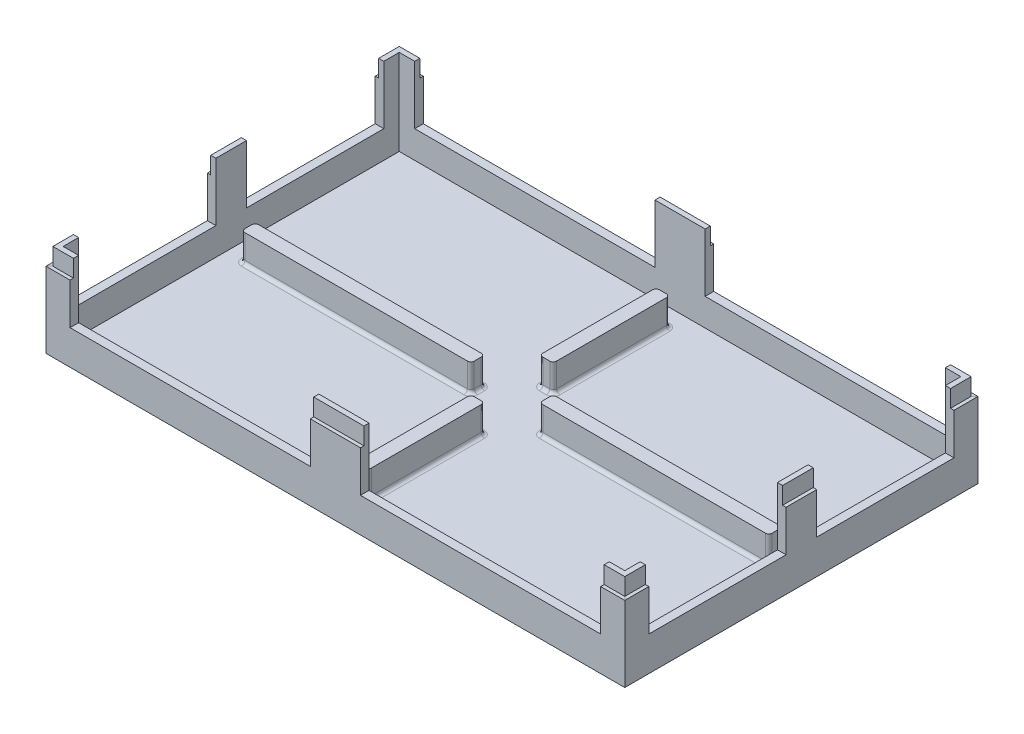
SolidWorks part; units mm, degrees
ref_plane "Front Plane" through (0, 0, 0) normal (0, 0, 1) x (1, 0, 0)
ref_plane "Top Plane" through (0, 0, 0) normal (0, 1, 0) x (1, 0, 0)
ref_plane "Right Plane" through (0, 0, 0) normal (1, 0, 0) x (0, 0, -1)
sketch "Sketch1" plane through (0, 0, 0) normal (0, 1, 0) x (1, 0, 0)
  line L0 (2, 48.96) -> (81.81, 48.96)
  line L1 (3, 47.46) -> (80.31, 47.46) construction
  line L2 (3, 47.46) -> (3, 3) construction
  line L3 (3, 3) -> (80.31, 3) construction
  line L4 (80.31, 47.46) -> (80.31, 3) construction
  line L5 (0, 50.46) -> (0, 60.2417) construction
  line L6 (80.31, -47.46) -> (80.31, -3) construction
  line L7 (3, -3) -> (80.31, -3) construction
  line L8 (3, -47.46) -> (3, -3) construction
  line L9 (3, -47.46) -> (80.31, -47.46) construction
  line L10 (-3, -47.46) -> (-80.31, -47.46) construction
  line L11 (-3, -47.46) -> (-3, -3) construction
  line L12 (-3, -3) -> (-80.31, -3) construction
  line L13 (-80.31, -47.46) -> (-80.31, -3) construction
  line L14 (-80.31, 47.46) -> (-80.31, 3) construction
  line L15 (-3, 3) -> (-80.31, 3) construction
  line L16 (-3, 47.46) -> (-3, 3) construction
  line L17 (-3, 47.46) -> (-80.31, 47.46) construction
  line L18 (-83.31, 50.46) -> (-83.31, -50.46)
  line L19 (2, -48.96) -> (81.81, -48.96)
  line L20 (-2, 48.96) -> (-2, 2)
  line L22 (2, 48.96) -> (2, 2)
  line L23 (81.81, 2) -> (2, 2)
  line L24 (-81.81, -48.96) -> (81.81, -48.96) construction
  line L25 (81.81, -2) -> (2, -2)
  line L26 (-2, -2) -> (-2, -48.96)
  line L27 (-81.81, 48.96) -> (-2, 48.96)
  line L28 (-81.81, 48.96) -> (-81.81, 2)
  line L29 (-81.81, -48.96) -> (-2, -48.96)
  line L30 (81.81, 48.96) -> (81.81, 2)
  line L31 (-83.31, -50.46) -> (83.31, -50.46)
  line L32 (83.31, 50.46) -> (83.31, -50.46)
  line L33 (-83.31, 50.46) -> (83.31, 50.46)
  line L34 (-81.81, -2) -> (-81.81, -48.96)
  line L35 (-81.81, 48.96) -> (-81.81, -48.96) construction
  line L36 (2, -2) -> (2, -48.96)
  line L37 (83.31, 0) -> (90.9815, 0) construction
  line L38 (-2, -2) -> (-81.81, -2)
  line L39 (-2, 2) -> (-81.81, 2)
  line L40 (81.81, -2) -> (81.81, -48.96)
  line L41 (81.81, 48.96) -> (81.81, -48.96) construction
  line L42 (-81.81, 48.96) -> (81.81, 48.96) construction
  dimension "D1" = 77.31
  dimension "D2" = 44.46
  dimension "D3" = 3
  dimension "D4" = 3
  dimension "D5" = 4
  dimension "D6" = 2
  dimension "D9" = 4
  dimension "D13" = 3
  dimension "D14" = 3
  dimension "D15" = 3
  dimension "D16" = 3
  dimension "D17" = 1.5
extrude "Boss-Extrude1" add sketch "Sketch1" along normal blind 25
sketch "Sketch2" plane through (0, 0, 0) normal (0, -1, 0) x (1, 0, 0)
  line L1 (-83.31, 50.46) -> (83.31, 50.46)
  line L2 (-83.31, 50.46) -> (-83.31, -50.46)
  line L3 (-83.31, -50.46) -> (83.31, -50.46)
  line L4 (83.31, 50.46) -> (83.31, -50.46)
extrude "Boss-Extrude2" add sketch "Sketch2" along normal blind 2
sketch "Sketch3" plane through (0, 0, 0) normal (0, 1, 0) x (1, 0, 0)
  line L0 (-81.81, 48.96) -> (-81.81, 2) construction
  line L1 (-10, 10) -> (10, 10)
  line L2 (-10, 10) -> (-10, -10)
  line L3 (-10, -10) -> (10, -10)
  line L4 (10, 10) -> (10, -10)
  line L5 (-81.81, 15) -> (-76.81, 15)
  line L6 (-81.81, 15) -> (-81.81, -15)
  line L7 (-81.81, -15) -> (-76.81, -15)
  line L8 (-76.81, 15) -> (-76.81, -15)
  line L9 (-2, 48.96) -> (-81.81, 48.96) construction
  line L10 (-12.5, 48.96) -> (12.5, 48.96)
  line L11 (-12.5, 48.96) -> (-12.5, 43.96)
  line L12 (-12.5, 43.96) -> (12.5, 43.96)
  line L13 (12.5, 48.96) -> (12.5, 43.96)
  line L14 (-81.81, -48.96) -> (-2, -48.96) construction
  line L15 (-12.5, -48.96) -> (12.5, -48.96)
  line L16 (-12.5, -48.96) -> (-12.5, -43.96)
  line L17 (-12.5, -43.96) -> (12.5, -43.96)
  line L18 (12.5, -48.96) -> (12.5, -43.96)
  line L19 (81.81, 2) -> (81.81, 48.96) construction
  line L20 (81.81, 15) -> (76.81, 15)
  line L21 (81.81, 15) -> (81.81, -15)
  line L22 (81.81, -15) -> (76.81, -15)
  line L23 (76.81, 15) -> (76.81, -15)
  dimension "D1" = 30
  dimension "D2" = 15
  dimension "D3" = 5
  dimension "D4" = 20
  dimension "D5" = 20
  dimension "D6" = 10
  dimension "D7" = 10
  dimension "D8" = 25
  dimension "D9" = 5
  dimension "D10" = 5
  dimension "D11" = 25
  dimension "D12" = 12.5
  dimension "D13" = 12.5
  dimension "D14" = 30
  dimension "D15" = 5
  dimension "D16" = 15
extrude "Cut-Extrude1" cut sketch "Sketch3" along normal through all
sketch "Sketch4" plane through (0, -2, 0) normal (0, -1, 0) x (1, 0, 0)
  line L4 (-83.31, 50.46) -> (-83.31, -50.46) construction
  line L5 (83.31, 50.46) -> (-83.31, 50.46) construction
  line L6 (83.31, -50.46) -> (83.31, 50.46) construction
  line L7 (-83.31, -50.46) -> (83.31, -50.46) construction
  line L8 (84.31, -51.46) -> (84.31, 51.46)
  line L9 (-84.31, -51.46) -> (84.31, -51.46)
  line L10 (-84.31, 51.46) -> (-84.31, -51.46)
  line L11 (84.31, 51.46) -> (-84.31, 51.46)
  line L12 (84.31, -51.46) -> (84.31, 51.46)
  line L13 (-84.31, -51.46) -> (84.31, -51.46)
  line L14 (-84.31, 51.46) -> (-84.31, -51.46)
  line L15 (84.31, 51.46) -> (-84.31, 51.46)
  line L16 (-83.31, 50.46) -> (-83.31, -50.46)
  line L17 (83.31, 50.46) -> (-83.31, 50.46)
  line L18 (83.31, -50.46) -> (83.31, 50.46)
  line L19 (-83.31, -50.46) -> (83.31, -50.46)
  dimension "D1" = 2.5
extrude "Boss-Extrude3" add sketch "Sketch4" against normal up to surface (27 mm away) up to face at (0, 25, 0)
fillet "Fillet1" radius 1 40 edges at (0, 0, -10) (0, 0, -43.96) (10, 0, 0) (76.81, 0, 0) (-10, 0, 0) (-76.81, 0, 0) (0, 0, 10) (0, 0, 43.96) (-10, 12.5, 2) (-43.405, 0, 2) (-76.81, 12.5, 2) (-43.405, 25, 2) (-2, 12.5, -10) (-2, 0, -26.98) (-2, 12.5, -43.96) (-2, 25, -26.98) (2, 12.5, -10) (2, 25, -26.98) (2, 12.5, -43.96) (2, 0, -26.98) (10, 12.5, -2) (43.405, 0, -2) (76.81, 12.5, -2) (43.405, 25, -2) (10, 12.5, 2) (43.405, 25, 2) (76.81, 12.5, 2) (43.405, 0, 2) (-2, 12.5, 10) (-2, 25, 26.98) (-2, 12.5, 43.96) (-2, 0, 26.98) (-10, 12.5, -2) (-43.405, 25, -2) (-76.81, 12.5, -2) (-43.405, 0, -2) (2, 12.5, 10) (2, 0, 26.98) (2, 12.5, 43.96) (2, 25, 26.98)
sketch "Sketch5" plane through (84.31, 0, 0) normal (1, 0, 0) x (0, 0, -1)
  line L0 (-51.46, 25) -> (-51.46, -2) construction
  line L1 (-50.46, 20) -> (-51.46, 20)
  line L2 (-50.46, 20) -> (-50.46, 25)
  line L3 (-50.46, 25) -> (-51.46, 25)
  line L4 (-51.46, 20) -> (-51.46, 25)
  line L5 (-51.46, 25) -> (51.46, 25) construction
  dimension "D1" = 0
  dimension "D2" = 0
  dimension "D3" = 1
  dimension "D4" = 5
sketch "Sketch7" plane through (0, 25, 0) normal (0, 1, 0) x (1, 0, 0)
  line L0 (-84.31, -51.46) -> (84.31, -51.46) construction
  line L1 (-84.31, -51.46) -> (84.31, -51.46)
  line L2 (-84.31, 51.46) -> (-84.31, -51.46) construction
  line L3 (84.31, 51.46) -> (-84.31, 51.46) construction
  line L4 (84.31, -51.46) -> (84.31, 51.46) construction
  line L5 (-84.31, 51.46) -> (-84.31, -51.46)
  line L6 (84.31, 51.46) -> (-84.31, 51.46)
  line L7 (84.31, -51.46) -> (84.31, 51.46)
sweep "Cut-Sweep1" cut profiles "Sketch5" path "Sketch7"
sketch "Sketch8" plane through (0, 0, 51.46) normal (0, 0, 1) x (1, 0, 0)
  line L0 (84.31, -2) -> (-84.31, -2) construction
  line L1 (-77.31, 52.0229) -> (-7.31, 52.0229)
  line L2 (-77.31, 52.0229) -> (-77.31, 8)
  line L3 (-77.31, 8) -> (-7.31, 8)
  line L4 (-7.31, 52.0229) -> (-7.31, 8)
  line L5 (7.31, 52.0229) -> (77.31, 52.0229)
  line L6 (7.31, 52.0229) -> (7.31, 8)
  line L7 (7.31, 8) -> (77.31, 8)
  line L8 (77.31, 52.0229) -> (77.31, 8)
  line L9 (-84.31, 20) -> (-84.31, -2) construction
  line L10 (84.31, 20) -> (84.31, -2) construction
  dimension "D1" = 10
  dimension "D2" = 10
  dimension "D3" = 7
  dimension "D4" = 70
  dimension "D5" = 7
  dimension "D6" = 70
extrude "Cut-Extrude2" cut sketch "Sketch8" against normal through all
sketch "Sketch9" plane through (84.31, 0, 0) normal (1, 0, 0) x (0, 0, -1)
  line L0 (-51.46, 20) -> (-51.46, -2) construction
  line L1 (-44.46, 29.6914) -> (-4.46, 29.6914)
  line L2 (-44.46, 29.6914) -> (-44.46, 8)
  line L3 (-44.46, 8) -> (-4.46, 8)
  line L4 (-4.46, 29.6914) -> (-4.46, 8)
  line L5 (51.46, -2) -> (-51.46, -2) construction
  line L6 (51.46, 20) -> (51.46, -2) construction
  line L7 (44.46, 29.6914) -> (4.46, 29.6914)
  line L8 (44.46, 29.6914) -> (44.46, 8)
  line L9 (44.46, 8) -> (4.46, 8)
  line L10 (4.46, 29.6914) -> (4.46, 8)
  dimension "D1" = 7
  dimension "D2" = 40
  dimension "D3" = 10
  dimension "D4" = 40
  dimension "D5" = 7
  dimension "D6" = 10
extrude "Cut-Extrude3" cut sketch "Sketch9" along normal blind 2 and the other way through all
